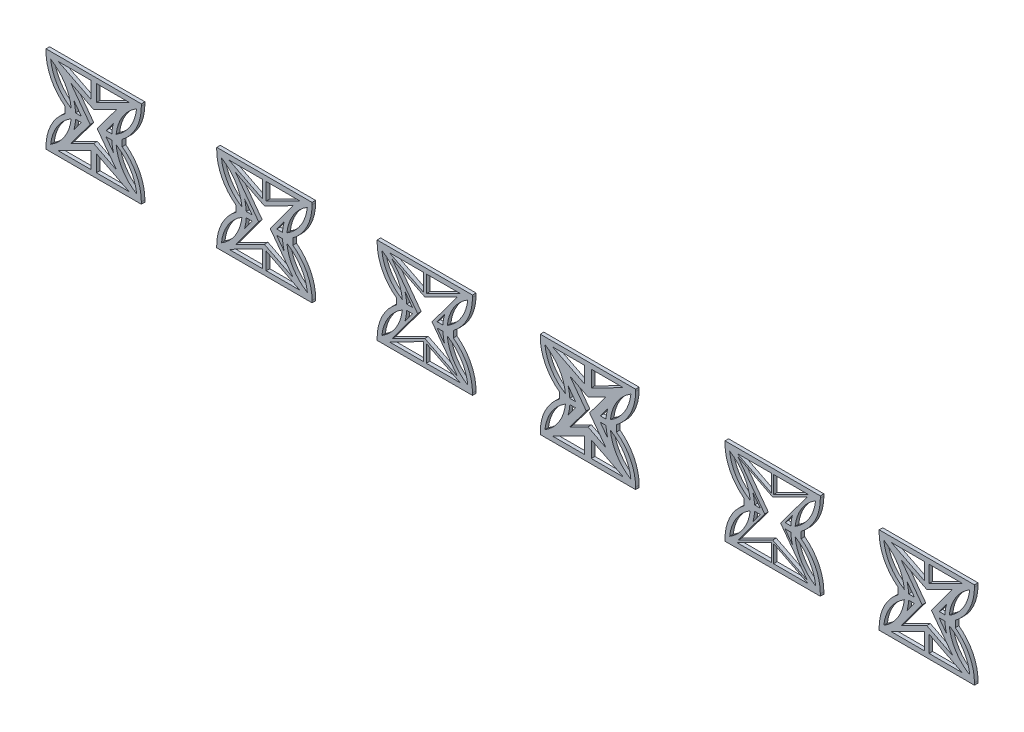
SolidWorks part; units mm, degrees
ref_plane "Front Plane" through (0, 0, 0) normal (0, 0, 1) x (1, 0, 0)
ref_plane "Top Plane" through (0, 0, 0) normal (0, 1, 0) x (1, 0, 0)
ref_plane "Right Plane" through (0, 0, 0) normal (1, 0, 0) x (0, 0, -1)
sketch "Sketch1" plane through (0, 0, 0) normal (0, 0, 1) x (1, 0, 0)
  line L0 (-8.4096, 11.0493) -> (-1.8517, 2.191)
  line L1 (-1.5869, -10.8666) -> (-12.6275, -10.8666)
  line L2 (7.0826, -6.6672) -> (0.5247, 2.191)
  line L3 (-4.8296, 3.1096) -> (-6.7785, 3.1096)
  line L4 (0.2599, 15.0871) -> (0.2599, 15.2487)
  line L5 (3.5026, 3.1096) -> (5.4515, 3.1096)
  line L6 (-1.5869, 15.2487) -> (-12.6275, 15.2487)
  line L7 (0.2599, -5.2903) -> (0.2599, -10.8666)
  line L8 (11.3005, 15.2487) -> (0.2599, 15.2487)
  line L9 (-1.5869, -5.2903) -> (-1.5869, -10.705)
  line L10 (7.0826, 11.0493) -> (0.5247, 2.191)
  line L11 (0.2599, 9.6724) -> (11.3005, 15.2487)
  line L12 (-10.302, 3.2711) -> (-10.302, 1.111)
  line L13 (0.2599, -5.2903) -> (11.3005, -10.8666)
  line L14 (-8.4096, -6.6672) -> (-1.8517, 2.191)
  line L15 (-4.8296, 1.2725) -> (-6.7785, 1.2725)
  line L16 (-1.5869, 9.6724) -> (-12.6275, 15.2487)
  line L17 (3.5026, 1.2725) -> (5.4515, 1.2725)
  line L18 (-0.6635, 7.137) -> (-8.4096, 11.0493)
  line L19 (-16.7635, 16.1672) -> (15.4365, 16.1672) construction
  line L20 (11.3005, -10.8666) -> (0.2599, -10.8666)
  line L21 (-0.6635, -2.7549) -> (-8.4096, -6.6672)
  line L22 (-1.5869, 15.0871) -> (-1.5869, 15.2487)
  line L23 (-1.5869, -10.705) -> (-1.5869, -10.8666)
  line L24 (-4.8296, 3.1096) -> (-7.3444, 6.5065)
  line L25 (0.2599, 9.6724) -> (0.2599, 15.0871)
  line L26 (8.975, 3.2711) -> (8.975, 1.111)
  line L27 (-1.5869, -5.2903) -> (-12.6275, -10.8666)
  line L28 (3.5026, 3.1096) -> (6.0174, 6.5065)
  line L29 (3.5026, 1.2725) -> (6.0174, -2.1244)
  line L30 (-0.6635, -2.7549) -> (7.0826, -6.6672)
  line L31 (-4.8296, 1.2725) -> (-7.3444, -2.1244)
  line L32 (-1.5869, 9.6724) -> (-1.5869, 15.0871)
  line L33 (-0.6635, 7.137) -> (7.0826, 11.0493)
  line L34 (-16.7635, -11.7851) -> (15.4365, -11.7851) construction
  line L35 (-16.7635, 16.1672) -> (-16.7635, 16.8836)
  line L36 (-16.7635, 16.8836) -> (15.4365, 16.8836)
  line L37 (15.4365, 16.8836) -> (15.4365, 16.1672)
  line L38 (-16.7635, -11.7851) -> (-16.7635, -12.5015)
  line L39 (-16.7635, -12.5015) -> (15.4365, -12.5015)
  line L40 (15.4365, -12.5015) -> (15.4365, -11.7851)
  line L41 (56.3821, 15.2487) -> (45.0415, 15.2487)
  line L42 (52.8394, 1.2725) -> (50.3246, -2.1244)
  line L43 (40.9055, -12.5015) -> (73.1055, -12.5015)
  line L47 (40.9055, 16.8836) -> (73.1055, 16.8836)
  line L48 (40.9055, -11.7851) -> (73.1055, -11.7851) construction
  line L49 (52.8394, 3.1096) -> (50.8905, 3.1096)
  line L53 (47.367, 3.2711) -> (47.367, 1.111)
  line L54 (40.9055, -11.7851) -> (40.9055, -12.5015)
  line L55 (56.3821, 9.5209) -> (45.0415, 15.2487)
  line L56 (61.1716, 3.1096) -> (63.6864, 6.5065)
  line L57 (61.1716, 1.2725) -> (63.1206, 1.2725)
  line L60 (52.8394, 1.2725) -> (50.8905, 1.2725)
  line L62 (57.629, 9.5209) -> (68.9696, 15.2487)
  line L66 (40.9055, 16.1672) -> (40.9055, 16.8836)
  line L69 (61.1716, 3.1096) -> (63.1206, 3.1096)
  line L71 (68.9696, 15.2487) -> (57.629, 15.2487)
  line L72 (73.1055, 16.8836) -> (73.1055, 16.1672)
  line L76 (52.8394, 3.1096) -> (50.3246, 6.5065)
  line L77 (61.1716, 1.2725) -> (63.6864, -2.1244)
  line L78 (73.1055, -12.5015) -> (73.1055, -11.7851)
  line L79 (40.9055, 16.1672) -> (73.1055, 16.1672) construction
  line L81 (66.644, 3.2711) -> (66.644, 1.111)
  line L82 (66.7388, 12.7251) -> (58.9402, 2.191)
  line L83 (66.7388, -8.343) -> (58.9402, 2.191)
  line L84 (57.0055, -3.4271) -> (66.7388, -8.343)
  line L85 (57.0055, -3.4271) -> (47.2722, -8.343)
  line L86 (47.2722, -8.343) -> (55.0708, 2.191)
  line L87 (47.2722, 12.7251) -> (55.0708, 2.191)
  line L88 (57.0055, 7.8092) -> (47.2722, 12.7251)
  line L89 (57.0055, 7.8092) -> (66.7388, 12.7251)
  line L90 (56.3821, 15.2487) -> (56.3821, 9.5209)
  line L91 (57.629, 15.2487) -> (57.629, 9.5209)
  line L92 (55.0708, 2.191) -> (58.9402, 2.191) construction
  line L93 (68.9696, -10.8666) -> (57.629, -10.8666)
  line L94 (57.629, -5.1388) -> (68.9696, -10.8666)
  line L95 (57.629, -10.8666) -> (57.629, -5.1388)
  line L96 (56.3821, -10.8666) -> (56.3821, -5.1388)
  line L97 (56.3821, -5.1388) -> (45.0415, -10.8666)
  line L98 (56.3821, -10.8666) -> (45.0415, -10.8666)
  line L101 (95.0906, -11.7851) -> (95.0906, -12.5015)
  line L102 (95.0906, 16.1672) -> (127.2906, 16.1672) construction
  line L103 (111.6906, 9.4586) -> (123.1546, 15.2487)
  line L105 (115.3567, 3.1096) -> (117.3056, 3.1096)
  line L106 (110.6906, 9.4586) -> (99.2266, 15.2487)
  line L107 (107.0245, 1.2725) -> (104.5097, -2.1244)
  line L108 (123.1546, 15.2487) -> (111.6906, 15.2487)
  line L109 (95.0906, 16.8836) -> (127.2906, 16.8836)
  line L111 (95.0906, 16.1672) -> (95.0906, 16.8836)
  line L112 (110.6906, 15.2487) -> (99.2266, 15.2487)
  line L115 (115.3567, 1.2725) -> (117.3056, 1.2725)
  line L119 (120.8291, 3.2711) -> (120.8291, 1.111)
  line L120 (127.2906, -12.5015) -> (127.2906, -11.7851)
  line L121 (95.0906, -11.7851) -> (127.2906, -11.7851) construction
  line L124 (115.3567, 3.1096) -> (117.8715, 6.5065)
  line L126 (115.3567, 1.2725) -> (117.8715, -2.1244)
  line L128 (127.2906, 16.8836) -> (127.2906, 16.1672)
  line L131 (107.0245, 1.2725) -> (105.0756, 1.2725)
  line L132 (95.0906, -12.5015) -> (127.2906, -12.5015)
  line L134 (101.5521, 3.2711) -> (101.5521, 1.111)
  line L135 (107.0245, 3.1096) -> (104.5097, 6.5065)
  line L137 (107.0245, 3.1096) -> (105.0756, 3.1096)
  line L140 (122.2487, 13.8423) -> (113.623, 2.191)
  line L141 (122.2487, -9.4602) -> (113.623, 2.191)
  line L142 (111.1906, -3.8752) -> (122.2487, -9.4602)
  line L143 (111.1906, -3.8752) -> (100.1325, -9.4602)
  line L144 (100.1325, -9.4602) -> (108.7582, 2.191)
  line L145 (100.1325, 13.8423) -> (108.7582, 2.191)
  line L146 (111.1906, 8.2573) -> (100.1325, 13.8423)
  line L147 (111.1906, 8.2573) -> (122.2487, 13.8423)
  line L148 (110.6906, 15.2487) -> (110.6906, 9.4586)
  line L149 (111.6906, 15.2487) -> (111.6906, 9.4586)
  line L150 (108.7582, 2.191) -> (113.623, 2.191) construction
  line L151 (111.6906, -5.0765) -> (123.1546, -10.8666)
  line L152 (111.6906, -10.8666) -> (111.6906, -5.0765)
  line L153 (123.1546, -10.8666) -> (111.6906, -10.8666)
  line L154 (110.6906, -10.8666) -> (110.6906, -5.0765)
  line L155 (110.6906, -5.0765) -> (99.2266, -10.8666)
  line L156 (110.6906, -10.8666) -> (99.2266, -10.8666)
  line L157 (232.8569, 1.2725) -> (234.8058, 1.2725)
  line L158 (212.5907, 16.1672) -> (212.5907, 16.8836)
  line L159 (244.7907, 16.8836) -> (244.7907, 16.1672)
  line L160 (224.5246, 1.2725) -> (222.5757, 1.2725)
  line L161 (212.5907, -11.7851) -> (212.5907, -12.5015)
  line L162 (224.5246, 3.1096) -> (222.0098, 6.5065)
  line L163 (212.5907, -12.5015) -> (244.7907, -12.5015)
  line L164 (219.0522, 3.2711) -> (219.0522, 1.111)
  line L165 (212.5907, 16.1672) -> (244.7907, 16.1672) construction
  line L166 (240.6548, 15.2487) -> (229.0142, 15.2487)
  line L167 (232.8569, 3.1096) -> (235.3716, 6.5065)
  line L168 (228.3673, 9.3694) -> (216.7267, 15.2487)
  line L169 (232.8569, 1.2725) -> (235.3716, -2.1244)
  line L170 (232.8569, 3.1096) -> (234.8058, 3.1096)
  line L171 (224.5246, 1.2725) -> (222.0098, -2.1244)
  line L172 (224.5246, 3.1096) -> (222.5757, 3.1096)
  line L173 (212.5907, 16.8836) -> (244.7907, 16.8836)
  line L174 (228.3673, 15.2487) -> (216.7267, 15.2487)
  line L175 (244.7907, -12.5015) -> (244.7907, -11.7851)
  line L176 (212.5907, -11.7851) -> (244.7907, -11.7851) construction
  line L177 (229.0142, 9.3694) -> (240.6548, 15.2487)
  line L178 (228.3673, 15.2487) -> (228.3673, 9.3694)
  line L179 (229.0142, 15.2487) -> (229.0142, 9.3694)
  line L180 (228.6907, -4.0992) -> (240.4112, -10.0189)
  line L181 (240.4112, -10.0189) -> (231.372, 2.191)
  line L182 (240.4112, 14.401) -> (231.372, 2.191)
  line L183 (228.6907, 8.4813) -> (240.4112, 14.401)
  line L184 (228.6907, 8.4813) -> (216.9702, 14.401)
  line L185 (216.9702, 14.401) -> (226.0094, 2.191)
  line L186 (216.9702, -10.0189) -> (226.0094, 2.191)
  line L187 (228.6907, -4.0992) -> (216.9702, -10.0189)
  line L188 (229.0142, -4.9873) -> (240.6548, -10.8666)
  line L189 (229.0142, -10.8666) -> (229.0142, -4.9873)
  line L190 (240.6548, -10.8666) -> (229.0142, -10.8666)
  line L191 (228.3673, -10.8666) -> (228.3673, -4.9873)
  line L192 (228.3673, -4.9873) -> (216.7267, -10.8666)
  line L193 (228.3673, -10.8666) -> (216.7267, -10.8666)
  line L194 (170.4547, 1.2725) -> (172.4036, 1.2725)
  line L195 (150.1886, 16.1672) -> (150.1886, 16.8836)
  line L196 (182.3886, 16.8836) -> (182.3886, 16.1672)
  line L197 (162.1224, 1.2725) -> (160.1735, 1.2725)
  line L198 (150.1886, -11.7851) -> (150.1886, -12.5015)
  line L199 (162.1224, 3.1096) -> (159.6077, 6.5065)
  line L200 (150.1886, -12.5015) -> (182.3886, -12.5015)
  line L201 (156.6501, 3.2711) -> (156.6501, 1.111)
  line L202 (150.1886, 16.1672) -> (182.3886, 16.1672) construction
  line L203 (178.2526, 15.2487) -> (167.462, 15.2487)
  line L204 (170.4547, 3.1096) -> (172.9695, 6.5065)
  line L205 (165.1151, 9.7987) -> (154.3245, 15.2487)
  line L206 (170.4547, 1.2725) -> (172.9695, -2.1244)
  line L207 (170.4547, 3.1096) -> (172.4036, 3.1096)
  line L208 (162.1224, 1.2725) -> (159.6077, -2.1244)
  line L209 (162.1224, 3.1096) -> (160.1735, 3.1096)
  line L210 (150.1886, 16.8836) -> (182.3886, 16.8836)
  line L211 (165.1151, 15.2487) -> (154.3245, 15.2487)
  line L212 (182.3886, -12.5015) -> (182.3886, -11.7851)
  line L213 (150.1886, -11.7851) -> (182.3886, -11.7851) construction
  line L214 (175.9271, 3.2711) -> (175.9271, 1.111)
  line L215 (167.462, 9.7987) -> (178.2526, 15.2487)
  line L216 (166.2886, -2.1947) -> (172.3787, -5.2706)
  line L217 (172.3787, -5.2706) -> (166.8547, 2.191)
  line L218 (172.3787, 9.6527) -> (166.8547, 2.191)
  line L219 (166.2886, 6.5768) -> (172.3787, 9.6527)
  line L220 (166.2886, 6.5768) -> (160.1984, 9.6527)
  line L221 (160.1984, 9.6527) -> (165.7225, 2.191)
  line L222 (160.1984, -5.2706) -> (165.7225, 2.191)
  line L223 (166.2886, -2.1947) -> (160.1984, -5.2706)
  line L224 (165.1151, 15.2487) -> (165.1151, 9.7987)
  line L225 (167.462, 15.2487) -> (167.462, 9.7987)
  line L226 (167.462, -10.8666) -> (167.462, -5.4166)
  line L227 (178.2526, -10.8666) -> (167.462, -10.8666)
  line L228 (167.462, -5.4166) -> (178.2526, -10.8666)
  line L229 (165.1151, -10.8666) -> (165.1151, -5.4166)
  line L230 (165.1151, -10.8666) -> (154.3245, -10.8666)
  line L231 (165.1151, -5.4166) -> (154.3245, -10.8666)
  line L232 (238.3292, 3.2711) -> (238.3292, 1.111)
  line L233 (-16.7635, -12.5015) -> (49983.2365, -12.5015) construction
  line L234 (284.9201, 1.2725) -> (286.869, 1.2725)
  line L235 (264.654, 16.1672) -> (264.654, 16.8836)
  line L236 (296.854, 16.8836) -> (296.854, 16.1672)
  line L237 (276.5878, 1.2725) -> (274.6389, 1.2725)
  line L238 (264.654, -11.7851) -> (264.654, -12.5015)
  line L239 (276.5878, 3.1096) -> (274.073, 6.5065)
  line L240 (264.654, -12.5015) -> (296.854, -12.5015)
  line L241 (271.1154, 3.2711) -> (271.1154, 1.111)
  line L242 (264.654, 16.1672) -> (296.854, 16.1672) construction
  line L243 (292.718, 15.2487) -> (281.5274, 15.2487)
  line L244 (284.9201, 3.1096) -> (287.4349, 6.5065)
  line L245 (279.9805, 9.5967) -> (268.7899, 15.2487)
  line L246 (284.9201, 1.2725) -> (287.4349, -2.1244)
  line L247 (284.9201, 3.1096) -> (286.869, 3.1096)
  line L248 (276.5878, 1.2725) -> (274.073, -2.1244)
  line L249 (276.5878, 3.1096) -> (274.6389, 3.1096)
  line L250 (264.654, 16.8836) -> (296.854, 16.8836)
  line L251 (279.9805, 15.2487) -> (268.7899, 15.2487)
  line L252 (296.854, -12.5015) -> (296.854, -11.7851)
  line L253 (264.654, -11.7851) -> (296.854, -11.7851) construction
  line L254 (290.3925, 3.2711) -> (290.3925, 1.111)
  line L255 (281.5274, 9.5967) -> (292.718, 15.2487)
  line L256 (280.754, 7.4731) -> (289.4937, 11.8872)
  line L257 (289.4937, 11.8872) -> (282.3154, 2.191)
  line L258 (289.4937, -7.5051) -> (282.3154, 2.191)
  line L259 (280.754, -3.091) -> (289.4937, -7.5051)
  line L260 (280.754, -3.091) -> (272.0142, -7.5051)
  line L261 (272.0142, -7.5051) -> (279.1925, 2.191)
  line L262 (272.0142, 11.8872) -> (279.1925, 2.191)
  line L263 (280.754, 7.4731) -> (272.0142, 11.8872)
  line L264 (279.9805, 15.2487) -> (279.9805, 9.5967)
  line L265 (281.5274, 15.2487) -> (281.5274, 9.5967)
  line L266 (281.5274, -5.2146) -> (292.718, -10.8666)
  line L267 (281.5274, -10.8666) -> (281.5274, -5.2146)
  line L268 (292.718, -10.8666) -> (281.5274, -10.8666)
  line L269 (279.9805, -10.8666) -> (279.9805, -5.2146)
  line L270 (279.9805, -5.2146) -> (268.7899, -10.8666)
  line L271 (279.9805, -10.8666) -> (268.7899, -10.8666)
  arc A0 (13.849, 14.6502) -> (6.9314, 3.708) centre (21.444, 2.191) ccw
  arc A1 (-8.2584, 3.708) -> (-15.176, 14.6502) centre (-0.6635, 16.1672) cw
  arc A2 (15.4365, 16.1672) -> (8.975, 3.2711) centre (-0.6635, 16.1672) cw
  arc A3 (-6.7785, 1.2725) -> (-7.3444, -2.1244) centre (-22.7709, 2.191) cw
  arc A4 (5.4515, 3.1096) -> (6.0174, 6.5065) centre (21.444, 2.191) cw
  arc A5 (-16.7635, 16.1672) -> (-10.302, 3.2711) centre (-0.6635, 16.1672) ccw
  arc A6 (8.975, 1.111) -> (15.4365, -11.7851) centre (-0.6635, -11.7851) cw
  arc A7 (13.849, -10.2681) -> (6.9314, 0.6741) centre (21.444, 2.191) cw
  arc A8 (-15.176, 14.6502) -> (-8.2584, 3.708) centre (-22.7709, 2.191) cw
  arc A9 (6.9314, 3.708) -> (13.849, 14.6502) centre (-0.6635, 16.1672) ccw
  arc A10 (-8.2584, 0.6741) -> (-15.176, -10.2681) centre (-0.6635, -11.7851) ccw
  arc A11 (-6.7785, 3.1096) -> (-7.3444, 6.5065) centre (-22.7709, 2.191) ccw
  arc A12 (6.9314, 0.6741) -> (13.849, -10.2681) centre (-0.6635, -11.7851) cw
  arc A13 (5.4515, 1.2725) -> (6.0174, -2.1244) centre (21.444, 2.191) ccw
  arc A14 (-10.302, 1.111) -> (-16.7635, -11.7851) centre (-0.6635, -11.7851) ccw
  arc A15 (-15.176, -10.2681) -> (-8.2584, 0.6741) centre (-22.7709, 2.191) ccw
  arc A16 (42.493, 14.6502) -> (49.4106, 3.708) centre (34.8981, 2.191) cw
  arc A17 (40.9055, 16.1672) -> (47.367, 3.2711) centre (57.0055, 16.1672) ccw
  arc A18 (63.1206, 1.2725) -> (63.6864, -2.1244) centre (79.113, 2.191) ccw
  arc A19 (73.1055, 16.1672) -> (66.644, 3.2711) centre (57.0055, 16.1672) cw
  arc A20 (49.4106, 0.6741) -> (42.493, -10.2681) centre (57.0055, -11.7851) ccw
  arc A21 (64.6004, 0.6741) -> (71.518, -10.2681) centre (57.0055, -11.7851) cw
  arc A22 (42.493, -10.2681) -> (49.4106, 0.6741) centre (34.8981, 2.191) ccw
  arc A23 (49.4106, 3.708) -> (42.493, 14.6502) centre (57.0055, 16.1672) cw
  arc A24 (47.367, 1.111) -> (40.9055, -11.7851) centre (57.0055, -11.7851) ccw
  arc A25 (50.8905, 1.2725) -> (50.3246, -2.1244) centre (34.8981, 2.191) cw
  arc A26 (50.8905, 3.1096) -> (50.3246, 6.5065) centre (34.8981, 2.191) ccw
  arc A27 (71.518, 14.6502) -> (64.6004, 3.708) centre (79.113, 2.191) ccw
  arc A28 (64.6004, 3.708) -> (71.518, 14.6502) centre (57.0055, 16.1672) ccw
  arc A29 (63.1206, 3.1096) -> (63.6864, 6.5065) centre (79.113, 2.191) cw
  arc A30 (71.518, -10.2681) -> (64.6004, 0.6741) centre (79.113, 2.191) cw
  arc A31 (66.644, 1.111) -> (73.1055, -11.7851) centre (57.0055, -11.7851) cw
  arc A32 (120.8291, 1.111) -> (127.2906, -11.7851) centre (111.1906, -11.7851) cw
  arc A33 (125.7031, 14.6502) -> (118.7855, 3.708) centre (133.2981, 2.191) ccw
  arc A34 (105.0756, 1.2725) -> (104.5097, -2.1244) centre (89.0832, 2.191) cw
  arc A35 (118.7855, 3.708) -> (125.7031, 14.6502) centre (111.1906, 16.1672) ccw
  arc A36 (118.7855, 0.6741) -> (125.7031, -10.2681) centre (111.1906, -11.7851) cw
  arc A37 (96.6781, 14.6502) -> (103.5957, 3.708) centre (89.0832, 2.191) cw
  arc A38 (101.5521, 1.111) -> (95.0906, -11.7851) centre (111.1906, -11.7851) ccw
  arc A39 (105.0756, 3.1096) -> (104.5097, 6.5065) centre (89.0832, 2.191) ccw
  arc A40 (95.0906, 16.1672) -> (101.5521, 3.2711) centre (111.1906, 16.1672) ccw
  arc A41 (125.7031, -10.2681) -> (118.7855, 0.6741) centre (133.2981, 2.191) cw
  arc A42 (103.5957, 3.708) -> (96.6781, 14.6502) centre (111.1906, 16.1672) cw
  arc A43 (117.3056, 3.1096) -> (117.8715, 6.5065) centre (133.2981, 2.191) cw
  arc A44 (103.5957, 0.6741) -> (96.6781, -10.2681) centre (111.1906, -11.7851) ccw
  arc A45 (127.2906, 16.1672) -> (120.8291, 3.2711) centre (111.1906, 16.1672) cw
  arc A46 (117.3056, 1.2725) -> (117.8715, -2.1244) centre (133.2981, 2.191) ccw
  arc A47 (96.6781, -10.2681) -> (103.5957, 0.6741) centre (89.0832, 2.191) ccw
  arc A48 (222.5757, 1.2725) -> (222.0098, -2.1244) centre (206.5833, 2.191) cw
  arc A49 (236.2856, 0.6741) -> (243.2032, -10.2681) centre (228.6907, -11.7851) cw
  arc A50 (214.1782, -10.2681) -> (221.0958, 0.6741) centre (206.5833, 2.191) ccw
  arc A51 (236.2856, 3.708) -> (243.2032, 14.6502) centre (228.6907, 16.1672) ccw
  arc A52 (244.7907, 16.1672) -> (238.3292, 3.2711) centre (228.6907, 16.1672) cw
  arc A53 (212.5907, 16.1672) -> (219.0522, 3.2711) centre (228.6907, 16.1672) ccw
  arc A54 (214.1782, 14.6502) -> (221.0958, 3.708) centre (206.5833, 2.191) cw
  arc A55 (221.0958, 0.6741) -> (214.1782, -10.2681) centre (228.6907, -11.7851) ccw
  arc A56 (243.2032, -10.2681) -> (236.2856, 0.6741) centre (250.7982, 2.191) cw
  arc A57 (222.5757, 3.1096) -> (222.0098, 6.5065) centre (206.5833, 2.191) ccw
  arc A58 (238.3292, 1.111) -> (244.7907, -11.7851) centre (228.6907, -11.7851) cw
  arc A59 (221.0958, 3.708) -> (214.1782, 14.6502) centre (228.6907, 16.1672) cw
  arc A60 (234.8058, 1.2725) -> (235.3716, -2.1244) centre (250.7982, 2.191) ccw
  arc A61 (234.8058, 3.1096) -> (235.3716, 6.5065) centre (250.7982, 2.191) cw
  arc A62 (219.0522, 1.111) -> (212.5907, -11.7851) centre (228.6907, -11.7851) ccw
  arc A63 (243.2032, 14.6502) -> (236.2856, 3.708) centre (250.7982, 2.191) ccw
  arc A64 (160.1735, 1.2725) -> (159.6077, -2.1244) centre (144.1811, 2.191) cw
  arc A65 (173.8835, 0.6741) -> (180.8011, -10.2681) centre (166.2886, -11.7851) cw
  arc A66 (151.776, -10.2681) -> (158.6936, 0.6741) centre (144.1811, 2.191) ccw
  arc A67 (173.8835, 3.708) -> (180.8011, 14.6502) centre (166.2886, 16.1672) ccw
  arc A68 (182.3886, 16.1672) -> (175.9271, 3.2711) centre (166.2886, 16.1672) cw
  arc A69 (150.1886, 16.1672) -> (156.6501, 3.2711) centre (166.2886, 16.1672) ccw
  arc A70 (151.776, 14.6502) -> (158.6936, 3.708) centre (144.1811, 2.191) cw
  arc A71 (158.6936, 0.6741) -> (151.776, -10.2681) centre (166.2886, -11.7851) ccw
  arc A72 (180.8011, -10.2681) -> (173.8835, 0.6741) centre (188.396, 2.191) cw
  arc A73 (160.1735, 3.1096) -> (159.6077, 6.5065) centre (144.1811, 2.191) ccw
  arc A74 (175.9271, 1.111) -> (182.3886, -11.7851) centre (166.2886, -11.7851) cw
  arc A75 (158.6936, 3.708) -> (151.776, 14.6502) centre (166.2886, 16.1672) cw
  arc A76 (172.4036, 1.2725) -> (172.9695, -2.1244) centre (188.396, 2.191) ccw
  arc A77 (172.4036, 3.1096) -> (172.9695, 6.5065) centre (188.396, 2.191) cw
  arc A78 (156.6501, 1.111) -> (150.1886, -11.7851) centre (166.2886, -11.7851) ccw
  arc A79 (180.8011, 14.6502) -> (173.8835, 3.708) centre (188.396, 2.191) ccw
  arc A80 (274.6389, 1.2725) -> (274.073, -2.1244) centre (258.6465, 2.191) cw
  arc A81 (266.2414, -10.2681) -> (273.159, 0.6741) centre (258.6465, 2.191) ccw
  arc A82 (288.3489, 3.708) -> (295.2665, 14.6502) centre (280.754, 16.1672) ccw
  arc A83 (296.854, 16.1672) -> (290.3925, 3.2711) centre (280.754, 16.1672) cw
  arc A84 (264.654, 16.1672) -> (271.1154, 3.2711) centre (280.754, 16.1672) ccw
  arc A85 (266.2414, 14.6502) -> (273.159, 3.708) centre (258.6465, 2.191) cw
  arc A86 (273.159, 0.6741) -> (266.2414, -10.2681) centre (280.754, -11.7851) ccw
  arc A87 (274.6389, 3.1096) -> (274.073, 6.5065) centre (258.6465, 2.191) ccw
  arc A88 (290.3925, 1.111) -> (296.854, -11.7851) centre (280.754, -11.7851) cw
  arc A89 (273.159, 3.708) -> (266.2414, 14.6502) centre (280.754, 16.1672) cw
  arc A90 (286.869, 1.2725) -> (287.4349, -2.1244) centre (302.8614, 2.191) ccw
  arc A91 (286.869, 3.1096) -> (287.4349, 6.5065) centre (302.8614, 2.191) cw
  arc A92 (271.1154, 1.111) -> (264.654, -11.7851) centre (280.754, -11.7851) ccw
  arc A93 (295.2665, 14.6502) -> (288.3489, 3.708) centre (302.8614, 2.191) ccw
  arc A94 (295.2665, -10.2681) -> (288.3489, 0.6741) centre (302.8614, 2.191) cw
  arc A95 (288.3489, 0.6741) -> (295.2665, -10.2681) centre (280.754, -11.7851) cw
  dimension "D7" = 16.1
  dimension "D8" = 14.5916
  dimension "D9" = 16.1
  dimension "D10" = 14.5916
  dimension "D11" = 16.1
  dimension "D12" = 14.5916
  dimension "D13" = 14.5916
  dimension "D14" = 0.7165
  dimension "D19" = 14.5916
  dimension "D20" = 14.5916
  dimension "D21" = 16.1
  dimension "D23" = 14.5916
  dimension "D24" = 16.1
  dimension "D25" = 14.5916
  dimension "D1" = 1.2469
  dimension "D2" = 1.2469
  dimension "D3" = 0.8469
  dimension "D4" = 0.8469
  dimension "D5" = 0.8469
  dimension "D6" = 1.8469
  dimension "D15" = 0.7165
  dimension "D16" = 0.7165
  dimension "D17" = 0.7165
  dimension "D18" = 2.3469
  dimension "D22" = 0.6469
  dimension "D26" = 0.7165
  dimension "D27" = 0.7165
extrude "Boss-Extrude1" add sketch "Sketch1" along normal blind 1.2
